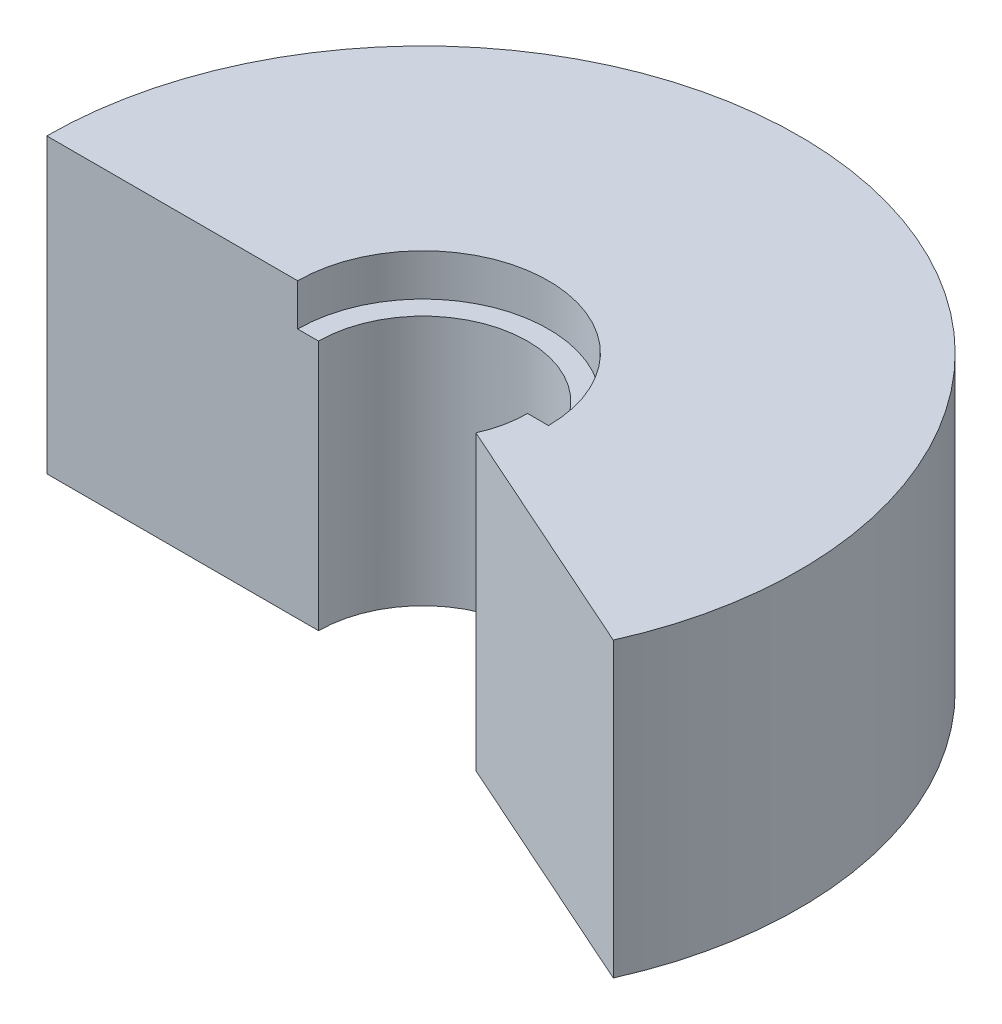
SolidWorks part; units mm, degrees
ref_plane "Front Plane" through (0, 0, 0) normal (0, 0, 1) x (1, 0, 0)
ref_plane "Top Plane" through (0, 0, 0) normal (0, 1, 0) x (1, 0, 0)
ref_plane "Right Plane" through (0, 0, 0) normal (1, 0, 0) x (0, 0, -1)
sketch "Sketch1" plane through (0, 0, 0) normal (0, 1, 0) x (1, 0, 0)
  circle A0 centre (0, 0) radius 9
  point P3 (0, 0)
extrude "Boss-Extrude1" add sketch "Sketch1" along normal blind 7
sketch "Sketch2" plane through (0, 7, 0) normal (0, 1, 0) x (1, 0, 0)
  circle A0 centre (0, 0) radius 2.5
sketch "Sketch16" plane through (0, 7, 0) normal (0, 1, 0) x (1, 0, 0)
  line L0 (-2.5, 0) -> (-9, 0)
  line L1 (2.2831, -1.0185) -> (2.2828, -1.0191)
  line L2 (2.2828, -1.0191) -> (8.2183, -3.6688)
  line L3 (-2.5, 0) -> (2.2828, -1.0191)
  circle A0 centre (0, 0) radius 2.5 construction
  circle A2 centre (0, 0) radius 9 construction
  arc A3 (-9, 0) -> (8.2167, -3.6724) centre (0, 0) ccw
  circle M13 centre (0, 0) radius 9
extrude "Cut-Extrude4" cut sketch "Sketch2" against normal blind 11 contours A0
extrude "Cut-Extrude5" cut sketch "Sketch16" against normal blind 14 contours L3 L0 L2 M13
sketch "Sketch23" plane through (0, 7, 0) normal (0, 1, 0) x (1, 0, 0)
  line L0 (-2.5, 0) -> (-9, 0) construction
  line L1 (-3, 0) -> (-2.5, 0)
  line L2 (2.5, 0) -> (3, 0)
  arc A0 (-3, 0) -> (3, 0) centre (0, 0) cw
  arc A1 (2.2828, -1.0191) -> (-2.5, 0) centre (0, 0) ccw construction
  arc A2 (-2.5, 0) -> (2.5, 0) centre (0, 0) cw
  arc M7 (-2.5, 0) -> (2.2828, -1.0191) centre (0, 0) cw
  line M10 (-9, 0) -> (-2.5, 0)
extrude "Cut-Extrude6" cut sketch "Sketch23" against normal blind 1 contours A0 L2 M10 M7
